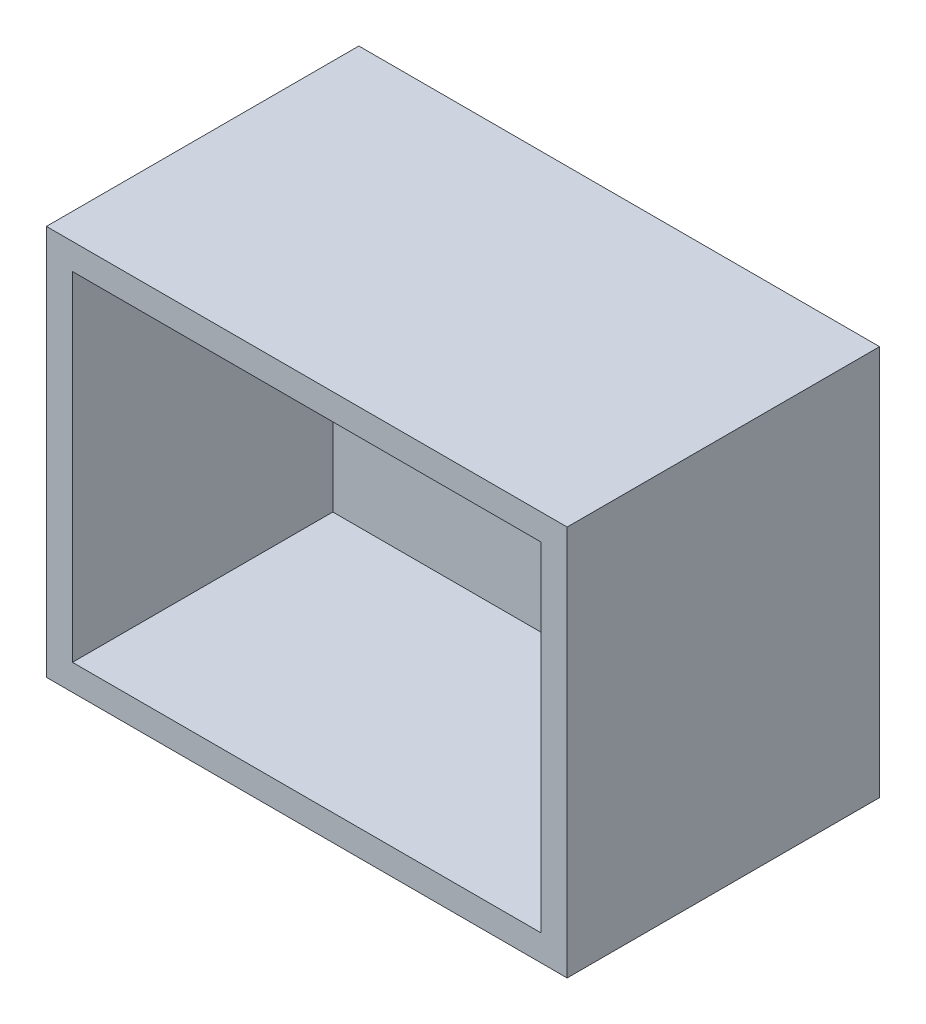
SolidWorks part; units mm, degrees
ref_plane "Vorne" through (0, 0, 0) normal (0, 0, 1) x (1, 0, 0)
ref_plane "Oben" through (0, 0, 0) normal (0, 1, 0) x (1, 0, 0)
ref_plane "Rechts" through (0, 0, 0) normal (1, 0, 0) x (0, 0, -1)
ref_plane "E_Boden" through (0, 1, 0) normal (0, 1, 0) x (1, 0, 0)
sketch "Skizze1" plane through (0, 0, 0) normal (0, 0, 1) x (1, 0, 0)
  line L0 (0, 15.1734) -> (0, -17.8902) construction
  line L1 (-25.2023, 0) -> (24.7977, 0) construction
  line L3 (-100, 75) -> (100, 75)
  line L4 (-100, 75) -> (-100, -75)
  line L5 (-100, -75) -> (100, -75)
  line L6 (100, 75) -> (100, -75)
  dimension "D1" = 200
  dimension "D2" = 150
extrude "Aufsatz-Linear austragen1" add sketch "Skizze1" along normal blind 120
sketch "Skizze2" plane through (0, 0, 120) normal (0, 0, 1) x (1, 0, 0)
  line L0 (0, 0) -> (0, 83.1968) construction
  line L1 (-90, 65) -> (90, 65)
  line L2 (-90, 65) -> (-90, -65)
  line L3 (-90, -65) -> (90, -65)
  line L4 (90, 65) -> (90, -65)
  line L5 (0, 83.1968) -> (0, -84.4401) construction
  line L6 (-126.6084, 0) -> (124.9507, 0) construction
  line L7 (100, 75) -> (-100, 75) construction
  line L8 (-100, 75) -> (-100, -75) construction
  dimension "D1" = 10
  dimension "D2" = 10
extrude "Schnitt-Linear austragen1" cut sketch "Skizze2" against normal blind 100
